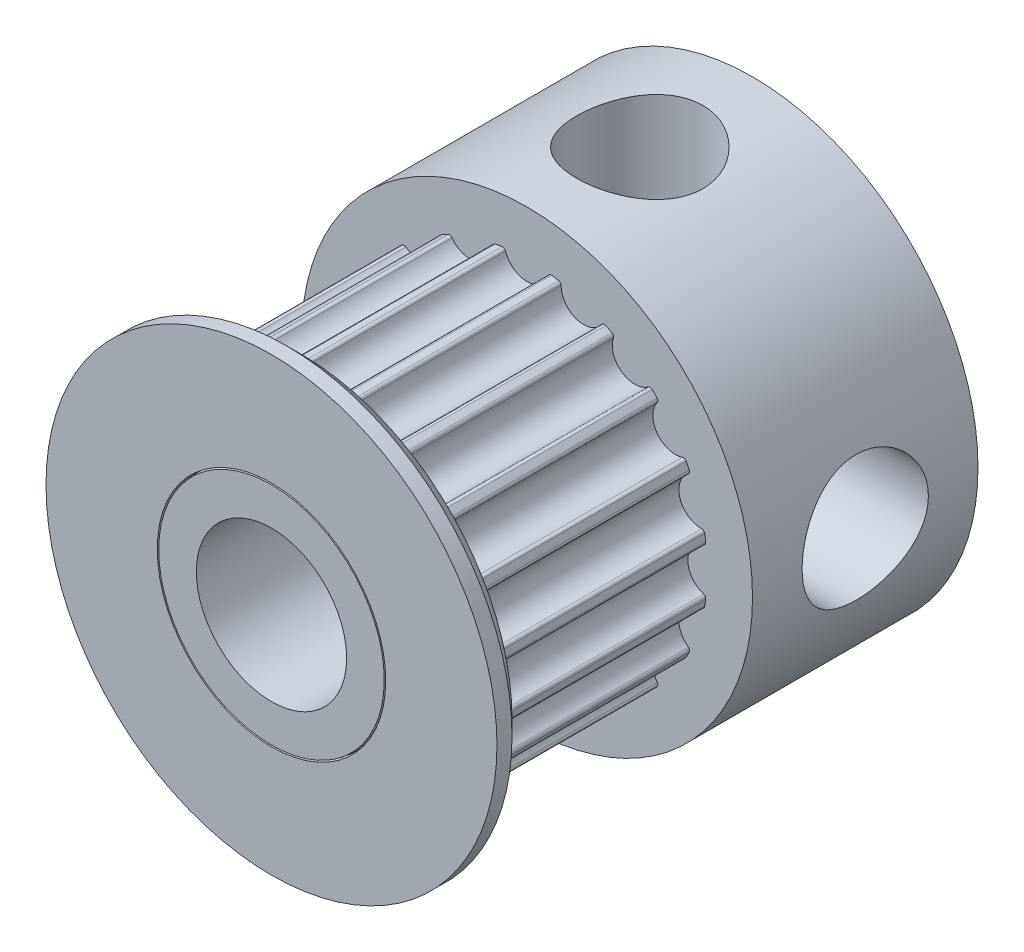
SolidWorks part; units mm, degrees
material "1060 Alloy"
ref_plane "Płaszczyzna przednia" through (0, 0, 0) normal (0, 0, 1) x (1, 0, 0)
ref_plane "Płaszczyzna górna" through (0, 0, 0) normal (0, 1, 0) x (1, 0, 0)
ref_plane "Płaszczyzna prawa" through (0, 0, 0) normal (1, 0, 0) x (0, 0, -1)
sketch "Sketch1" plane through (0, 0, 0) normal (0, 0, 1) x (1, 0, 0)
  circle A0 centre (0, 0) radius 7.5
  dimension "D1" = 15
extrude "Boss-Extrude1" add sketch "Sketch1" along normal blind 7.5
sketch "Sketch2" plane through (0, 0, 7.5) normal (0, 0, 1) x (1, 0, 0)
  circle A0 centre (0, 0) radius 6.1 construction
  circle A1 centre (0, 0) radius 6
  dimension "D1" = 12.2
  dimension "D2" = 12
extrude "Boss-Extrude2" add sketch "Sketch2" along normal blind 7.5
sketch "Sketch3" plane through (0, 0, 15) normal (0, 0, 1) x (1, 0, 0)
  line L0 (0, 6.1) -> (0, 0) construction
  line L1 (0, 5.35) -> (0, 6.1) construction
  circle A0 centre (0, 0) radius 6.1 construction
  circle A1 centre (0, 6.1) radius 0.75
  circle A2 centre (1.885, 5.8014) radius 0.75
  circle A3 centre (3.5855, 4.935) radius 0.75
  circle A4 centre (4.935, 3.5855) radius 0.75
  circle A5 centre (5.8014, 1.885) radius 0.75
  circle A6 centre (6.1, 0) radius 0.75
  circle A7 centre (5.8014, -1.885) radius 0.75
  circle A8 centre (4.935, -3.5855) radius 0.75
  circle A9 centre (3.5855, -4.935) radius 0.75
  circle A10 centre (1.885, -5.8014) radius 0.75
  circle A11 centre (0, -6.1) radius 0.75
  circle A12 centre (-1.885, -5.8014) radius 0.75
  circle A13 centre (-3.5855, -4.935) radius 0.75
  circle A14 centre (-4.935, -3.5855) radius 0.75
  circle A15 centre (-5.8014, -1.885) radius 0.75
  circle A16 centre (-6.1, 0) radius 0.75
  circle A17 centre (-5.8014, 1.885) radius 0.75
  circle A18 centre (-4.935, 3.5855) radius 0.75
  circle A19 centre (-3.5855, 4.935) radius 0.75
  circle A20 centre (-1.885, 5.8014) radius 0.75
  point P46 (0, 0)
  dimension "D1" = 12.2
  dimension "D3" = 0.75
  dimension "D2" = 20
extrude "Cut-Extrude1" cut sketch "Sketch3" against normal up to surface (7.5 mm away) up to face at (6, 0, 7.5)
fillet "Fillet1" radius 0.1 40 edges at (-2.5399, 5.4359, 11.25) (-1.1403, 5.8906, 11.25) (-4.0954, 4.385, 11.25) (-2.9048, 5.25, 11.25) (-5.25, 2.9048, 11.25) (-4.385, 4.0954, 11.25) (-5.8906, 1.1403, 11.25) (-5.4359, 2.5399, 11.25) (-5.9547, -0.7358, 11.25) (-5.9547, 0.7358, 11.25) (-5.4359, -2.5399, 11.25) (-5.8906, -1.1403, 11.25) (-4.385, -4.0954, 11.25) (-5.25, -2.9048, 11.25) (-2.9048, -5.25, 11.25) (-4.0954, -4.385, 11.25) (-1.1403, -5.8906, 11.25) (-2.5399, -5.4359, 11.25) (0.7358, -5.9547, 11.25) (-0.7358, -5.9547, 11.25) (2.5399, -5.4359, 11.25) (1.1403, -5.8906, 11.25) (4.0954, -4.385, 11.25) (2.9048, -5.25, 11.25) (5.25, -2.9048, 11.25) (4.385, -4.0954, 11.25) (5.8906, -1.1403, 11.25) (5.4359, -2.5399, 11.25) (5.9547, 0.7358, 11.25) (5.9547, -0.7358, 11.25) (5.4359, 2.5399, 11.25) (5.8906, 1.1403, 11.25) (4.385, 4.0954, 11.25) (5.25, 2.9048, 11.25) (2.9048, 5.25, 11.25) (4.0954, 4.385, 11.25) (1.1403, 5.8906, 11.25) (2.5399, 5.4359, 11.25) (-0.7358, 5.9547, 11.25) (0.7358, 5.9547, 11.25)
sketch "Sketch4" plane through (0, 0, 15) normal (0, 0, 1) x (1, 0, 0)
  circle A1 centre (0, 0) radius 7.5
  circle A2 centre (0, 0) radius 7.5
  dimension "D1" = 0
extrude "Boss-Extrude3" add sketch "Sketch4" along normal blind 1
chamfer "Chamfer1" distance 0.5 angle 45 1 edges at (7.5, 0, 15)
sketch "Sketch5" plane through (0, 0, 16) normal (0, 0, 1) x (1, 0, 0)
  circle A0 centre (0, 0) radius 2.5
  dimension "D1" = 5
extrude "Cut-Extrude2" cut sketch "Sketch5" against normal up to next
ref_plane "Plane1" through (0, 7.5, 0) normal (0, 1, 0) x (1, 0, 0)
hole_wizard "M5 Tapped Hole1" positions "Sketch6" profile "Sketch7" tap size "M5" standard "ISO"
sketch "Sketch6" plane through (0, 7.5, 0) normal (0, 1, 0) x (1, 0, 0)
  line L0 (0, -7.5) -> (0, 0) construction
  line L1 (0, 0) -> (0, -7.5) construction
  line L2 (-0.7152, -7.5) -> (0.7152, -7.5) construction
  point P0 (0, -3.75)
  point P12 (0, -3.75)
sketch "Sketch7" plane through (0, 7.5, 3.75) normal (1, 0, 0) x (0, 0, 1)
  line L0 (0, 0) -> (0, 15)
  line L1 (0, 15) -> (2.1, 15)
  line L2 (2.1, 15) -> (2.1, 0)
  line L5 (2.1, 0) -> (0, 0)
  line L11 (0, -6.35) -> (0, 107.95) construction
  dimension "Thru Tap Drill Dia." = 4.2
  dimension "Thru Tap Drill Depth" = 15
cosmetic thread "Hole Thread1" parameters "D2"=5
pattern_circular "CirPattern3" count 2 every 90 about axis through (0, 0, 7.5) along (0, 0, -1) of "M5 Tapped Hole1"
sketch "Sketch8" plane through (0, 0, 0) normal (0, 1, 0) x (1, 0, 0)
  line L0 (-3.75, 0) -> (-3.775, -0.15)
  line L1 (7.5, 0) -> (-7.5, 0) construction
  line L2 (-3.775, -0.15) -> (-3.8, 0)
  line L3 (-3.8, 0) -> (-3.75, 0)
  line L4 (-3.75, 0) -> (0, 0) construction
  line L5 (2.5, 0) -> (-2.5, 0) construction
  line L6 (-3.775, -0.15) -> (-3.775, 0) construction
  dimension "D1" = 0.05
  dimension "D2" = 0.15
  dimension "D3" = 3.75
revolve "Cut-Revolve1" cut sketch "Sketch8" angle 360 about axis through (0, 0, 7.5) along (0, 0, -1)
ref_plane "Plane2" through (0, 0, 8) normal (0, 0, -1) x (-1, 0, 0)
mirror "Mirror1" about plane through (0, 0, 8) normal (0, 0, -1) of "Cut-Revolve1"
